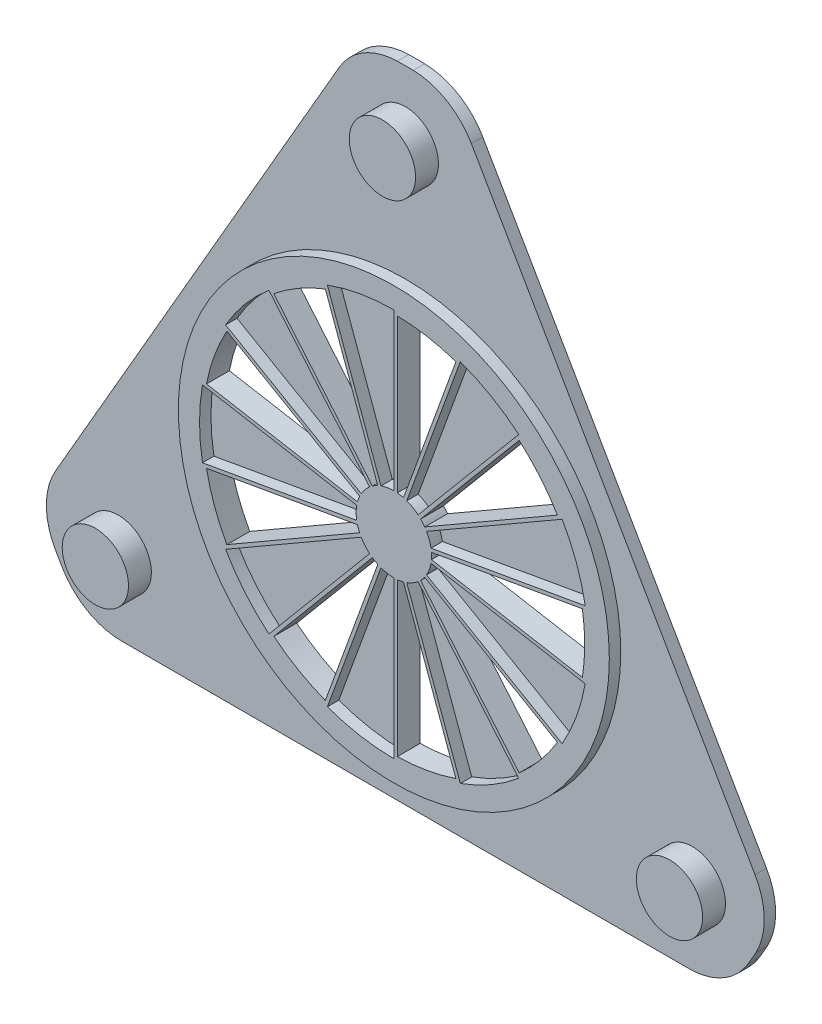
SolidWorks part; units mm, degrees
ref_plane "Спереди" through (0, 0, 0) normal (0, 0, 1) x (1, 0, 0)
ref_plane "Сверху" through (0, 0, 0) normal (0, 1, 0) x (1, 0, 0)
ref_plane "Справа" through (0, 0, 0) normal (1, 0, 0) x (0, 0, -1)
sketch "Sketch1" plane through (0, 0, 0) normal (0, 0, 1) x (1, 0, 0)
  line L0 (3.9, 6.755) -> (7.8, 0) construction
  line L2 (5.85, 10.1325) -> (11.7, 0) construction
  line L4 (7.8, 13.51) -> (15.6, 0) construction
  circle A61 centre (0, 0) radius 20
  circle A131 centre (0, 0) radius 1.25
  circle A484 centre (3.9, 0) radius 1.25
  circle A485 centre (7.8, 0) radius 1.25
  circle A486 centre (11.7, 0) radius 1.25
  circle A487 centre (15.6, 0) radius 1.25
  circle A488 centre (1.95, -3.3775) radius 1.25
  circle A489 centre (3.9, -6.755) radius 1.25
  circle A490 centre (5.85, -10.1325) radius 1.25
  circle A491 centre (7.8, -13.51) radius 1.25
  circle A492 centre (-1.95, -3.3775) radius 1.25
  circle A493 centre (-3.9, -6.755) radius 1.25
  circle A494 centre (-5.85, -10.1325) radius 1.25
  circle A495 centre (-7.8, -13.51) radius 1.25
  circle A496 centre (-3.9, 0) radius 1.25
  circle A497 centre (-7.8, 0) radius 1.25
  circle A498 centre (-11.7, 0) radius 1.25
  circle A499 centre (-15.6, 0) radius 1.25
  circle A500 centre (-1.95, 3.3775) radius 1.25
  circle A501 centre (-3.9, 6.755) radius 1.25
  circle A502 centre (-5.85, 10.1325) radius 1.25
  circle A503 centre (-7.8, 13.51) radius 1.25
  circle A504 centre (1.95, 3.3775) radius 1.25
  circle A505 centre (3.9, 6.755) radius 1.25
  circle A506 centre (5.85, 10.1325) radius 1.25
  circle A507 centre (7.8, 13.51) radius 1.25
  circle A508 centre (5.85, 3.3775) radius 1.25
  circle A509 centre (7.8, 6.755) radius 1.25
  circle A510 centre (9.75, 3.3775) radius 1.25
  circle A511 centre (11.7, 6.755) radius 1.25
  circle A512 centre (9.7491, 10.1341) radius 1.25
  circle A513 centre (13.6509, 3.3759) radius 1.25
  circle A514 centre (5.85, -3.3791) radius 1.25
  circle A515 centre (9.75, -3.3791) radius 1.25
  circle A516 centre (7.8, -6.7566) radius 1.25
  circle A517 centre (11.7, -6.7566) radius 1.25
  circle A518 centre (9.7491, -10.1356) radius 1.25
  circle A519 centre (13.6509, -3.3775) radius 1.25
  circle A520 centre (-0.0013, -6.7573) radius 1.25
  circle A521 centre (1.9487, -10.1348) radius 1.25
  circle A522 centre (-1.9513, -10.1348) radius 1.25
  circle A523 centre (-0.0013, -13.5123) radius 1.25
  circle A524 centre (-3.9032, -13.5123) radius 1.25
  circle A525 centre (3.9005, -13.5123) radius 1.25
  circle A526 centre (-5.8527, -3.3791) radius 1.25
  circle A527 centre (-7.8027, -6.7566) radius 1.25
  circle A528 centre (-9.7527, -3.3791) radius 1.25
  circle A529 centre (-11.7027, -6.7566) radius 1.25
  circle A530 centre (-13.6536, -3.3775) radius 1.25
  circle A531 centre (-9.7518, -10.1356) radius 1.25
  circle A532 centre (-5.8527, 3.3775) radius 1.25
  circle A533 centre (-9.7527, 3.3775) radius 1.25
  circle A534 centre (-7.8027, 6.755) radius 1.25
  circle A535 centre (-11.7027, 6.755) radius 1.25
  circle A536 centre (-9.7518, 10.1341) radius 1.25
  circle A537 centre (-13.6536, 3.3759) radius 1.25
  circle A538 centre (-0.0014, 6.7558) radius 1.25
  circle A539 centre (-1.9514, 10.1333) radius 1.25
  circle A540 centre (1.9486, 10.1333) radius 1.25
  circle A541 centre (-0.0014, 13.5108) radius 1.25
  circle A542 centre (3.9005, 13.5108) radius 1.25
  circle A543 centre (-3.9032, 13.5108) radius 1.25
  circle A544 centre (13.65, -1.1258) radius 2.2517 construction
  circle A545 centre (11.7009, -4.5044) radius 2.2522 construction
  circle A546 centre (9.75, -7.8834) radius 2.2522 construction
  circle A547 centre (7.7987, -11.2591) radius 2.2509 construction
  circle A548 centre (13.65, -1.1258) radius 0.65
  circle A549 centre (11.7009, -4.5044) radius 0.65
  circle A550 centre (9.75, -7.8834) radius 0.65
  circle A551 centre (7.7987, -11.2591) radius 0.65
  circle A552 centre (9.75, -1.1258) radius 0.65
  circle A553 centre (7.8009, -4.5044) radius 0.65
  circle A554 centre (5.85, -7.8834) radius 0.65
  circle A555 centre (3.8987, -11.2591) radius 0.65
  circle A556 centre (5.85, -1.1258) radius 0.65
  circle A557 centre (3.9009, -4.5044) radius 0.65
  circle A558 centre (1.95, -7.8834) radius 0.65
  circle A559 centre (-0.0013, -11.2591) radius 0.65
  circle A560 centre (1.95, -1.1258) radius 0.65
  circle A561 centre (0.0009, -4.5044) radius 0.65
  circle A562 centre (-1.95, -7.8834) radius 0.65
  circle A563 centre (-3.9013, -11.2591) radius 0.65
  circle A564 centre (-1.95, -1.1258) radius 0.65
  circle A565 centre (-3.8991, -4.5044) radius 0.65
  circle A566 centre (-5.85, -7.8834) radius 0.65
  circle A567 centre (-7.8013, -11.2591) radius 0.65
  circle A568 centre (-5.85, -1.1258) radius 0.65
  circle A569 centre (-7.7991, -4.5044) radius 0.65
  circle A570 centre (-9.75, -7.8834) radius 0.65
  circle A572 centre (-9.75, -1.1258) radius 0.65
  circle A573 centre (-11.6991, -4.5044) radius 0.65
  circle A576 centre (-13.65, -1.1258) radius 0.65
  circle A587 centre (0, 2.2517) radius 2.2517 construction
  circle A588 centre (0, 2.2517) radius 0.65
  circle A589 centre (3.9, 2.2517) radius 0.65
  circle A590 centre (7.8, 2.2517) radius 0.65
  circle A591 centre (11.7, 2.2517) radius 0.65
  circle A592 centre (15.6, 2.2517) radius 0.65
  circle A593 centre (1.9491, 5.6297) radius 2.2522 construction
  circle A594 centre (1.9491, 5.6297) radius 0.65
  circle A595 centre (5.8491, 5.6297) radius 0.65
  circle A596 centre (9.7491, 5.6297) radius 0.65
  circle A597 centre (13.6491, 5.6297) radius 0.65
  circle A598 centre (3.8991, 9.0072) radius 2.2522 construction
  circle A599 centre (3.8991, 9.0072) radius 0.65
  circle A600 centre (7.7991, 9.0072) radius 0.65
  circle A601 centre (11.6991, 9.0072) radius 0.65
  circle A602 centre (5.85, 12.3842) radius 2.2517 construction
  circle A603 centre (5.85, 12.3842) radius 0.65
  circle A604 centre (9.75, 12.3842) radius 0.65
  circle A605 centre (5.85, -14.6358) radius 0.65
  circle A606 centre (1.9509, -14.6353) radius 0.65
  circle A607 centre (-1.9491, -14.6353) radius 0.65
  circle A608 centre (-5.85, -14.6358) radius 0.65
  circle A609 centre (-15.6, 2.2517) radius 0.65
  circle A610 centre (-13.65, 5.6281) radius 0.65
  circle A611 centre (-11.7, 9.0056) radius 0.65
  circle A612 centre (-9.75, 12.3842) radius 0.65
  circle A613 centre (-5.85, 12.3842) radius 0.65
  circle A614 centre (-1.95, 12.3842) radius 0.65
  circle A615 centre (1.95, 12.3842) radius 0.65
  circle A616 centre (-7.8, 9.0056) radius 0.65
  circle A617 centre (-9.75, 5.6281) radius 0.65
  circle A618 centre (-11.7, 2.2517) radius 0.65
  circle A619 centre (-3.9, 9.0056) radius 0.65
  circle A620 centre (-5.85, 5.6281) radius 0.65
  circle A621 centre (-7.8, 2.2517) radius 0.65
  circle A622 centre (0, 9.0056) radius 0.65
  circle A623 centre (-1.95, 5.6281) radius 0.65
  circle A624 centre (-3.9, 2.2517) radius 0.65
  circle A625 centre (-15.5991, -4.5044) radius 0.65
  circle A626 centre (-13.65, -7.8834) radius 0.65
  circle A627 centre (-17.55, -7.8834) radius 0.65
  circle A628 centre (-19.5013, -11.2591) radius 0.65
  circle A629 centre (-15.6013, -11.2591) radius 0.65
  circle A630 centre (-11.7013, -11.2591) radius 0.65
  point P51 (0, 0)
  point P125 (-0.0013, -0.0008)
  point P231 (0, 0)
  dimension "D1" = 5
  dimension "D3" = 6
  dimension "D5" = 8
  dimension "D7" = 4
  dimension "D11" = 4
  dimension "D2" = 6
  dimension "D6" = 5
  dimension "D8" = 3
  dimension "D9" = 2
  dimension "D4" = 1.3
  dimension "D10" = 3
ref_plane "Plane1" through (0, 0, 10) normal (0, 0, 1) x (1, 0, 0)
sketch "Sketch2" plane through (0, 0, 10) normal (0, 0, 1) x (1, 0, 0)
  line L0 (0, 2.9883) -> (0, 17)
  line L62 (1.0221, 2.8081) -> (5.8143, 15.9748)
  line L71 (1.9208, 2.2892) -> (10.9274, 13.0228)
  line L92 (2.588, 1.4942) -> (14.7224, 8.5)
  line L101 (2.9429, 0.5189) -> (16.7417, 2.952)
  line L110 (2.9429, -0.5189) -> (16.7417, -2.952)
  line L119 (2.588, -1.4942) -> (14.7224, -8.5)
  line L124 (1.9208, -2.2892) -> (10.9274, -13.0228)
  line L133 (1.0221, -2.8081) -> (5.8143, -15.9748)
  line L142 (0, -2.9883) -> (0, -17)
  line L151 (-1.0221, -2.8081) -> (-5.8143, -15.9748)
  line L160 (-1.9208, -2.2892) -> (-10.9274, -13.0228)
  line L165 (-2.588, -1.4942) -> (-14.7224, -8.5)
  line L168 (-2.9429, -0.5189) -> (-16.7417, -2.952)
  line L171 (-2.9429, 0.5189) -> (-16.7417, 2.952)
  line L174 (-2.588, 1.4942) -> (-14.7224, 8.5)
  line L177 (-1.9208, 2.2892) -> (-10.9274, 13.0228)
  line L180 (-1.0221, 2.8081) -> (-5.8143, 15.9748)
  line L183 (0.3, 3.2863) -> (0.3, 16.6948)
  line L185 (5.4281, 15.7906) -> (0.8421, 3.1908)
  line L186 (14.3082, 8.6072) -> (2.696, 1.903)
  line L187 (2.3422, 2.3246) -> (10.9611, 12.5962)
  line L188 (16.4933, -2.6036) -> (3.2885, -0.2752)
  line L189 (3.2885, 0.2752) -> (16.4933, 2.6036)
  line L190 (10.9611, -12.5962) -> (2.3422, -2.3246)
  line L191 (2.696, -1.903) -> (14.3082, -8.6072)
  line L192 (0.3, -16.6948) -> (0.3, -3.2863)
  line L193 (0.8421, -3.1908) -> (5.4281, -15.7906)
  line L194 (-10.5014, -12.9818) -> (-1.8826, -2.7103)
  line L195 (-1.4059, -2.9855) -> (-5.9919, -15.5854)
  line L196 (-16.3891, -3.1945) -> (-3.1843, -0.8661)
  line L197 (-2.996, -1.3834) -> (-14.6082, -8.0876)
  line L198 (-14.6082, 8.0876) -> (-2.996, 1.3834)
  line L199 (-3.1843, 0.8661) -> (-16.3891, 3.1945)
  line L200 (-5.9919, 15.5854) -> (-1.4059, 2.9855)
  line L201 (-1.8826, 2.7103) -> (-10.5014, 12.9818)
  circle A52 centre (0, 0) radius 17
  circle A53 centre (0, 0) radius 18.85
  circle A199 centre (0, 0) radius 2.9883
  circle A245 centre (0, 0) radius 18.85
  circle A246 centre (0, 0) radius 3.3
  circle A247 centre (0, 0) radius 16.6975
  point P39 (0, 0)
  point P80 (0, 0)
  point P108 (0, 0)
  dimension "D1" = 18
  dimension "D4" = 9
  dimension "D2" = 0.3
  dimension "D3" = 0.3
extrude "Boss-Extrude1" add sketch "Sketch2" against normal blind 2
sketch "Sketch11" plane through (0, 0, 8) normal (0, 0, -1) x (-1, 0, 0)
  line L0 (0, 2.9883) -> (0, 18.85)
  line L1 (1.0221, 2.8081) -> (6.4471, 17.7132)
  line L2 (2.588, 1.4942) -> (16.3246, 9.425)
  line L3 (1.9208, 2.2892) -> (12.1165, 14.4399)
  line L4 (2.9429, -0.5189) -> (18.5636, -3.2733)
  line L5 (2.9429, 0.5189) -> (18.5636, 3.2733)
  line L6 (1.9208, -2.2892) -> (12.1165, -14.4399)
  line L7 (2.588, -1.4942) -> (16.3246, -9.425)
  line L8 (0, -2.9883) -> (0, -18.85)
  line L9 (1.0221, -2.8081) -> (6.4471, -17.7132)
  line L10 (-1.9208, -2.2892) -> (-12.1165, -14.4399)
  line L11 (-1.0221, -2.8081) -> (-6.4471, -17.7132)
  line L12 (-2.9429, -0.5189) -> (-18.5636, -3.2733)
  line L13 (-2.588, -1.4942) -> (-16.3246, -9.425)
  line L14 (-2.588, 1.4942) -> (-16.3246, 9.425)
  line L15 (-2.9429, 0.5189) -> (-18.5636, 3.2733)
  line L16 (-1.0221, 2.8081) -> (-6.4471, 17.7132)
  line L17 (-1.9208, 2.2892) -> (-12.1165, 14.4399)
  circle A0 centre (0, 0) radius 2.9883
  circle A5 centre (0, 0) radius 18.85 construction
  arc A6 (0, 18.85) -> (6.4471, 17.7132) centre (0, 0) cw
  arc A8 (12.1165, 14.4399) -> (16.3246, 9.425) centre (0, 0) cw
  arc A10 (18.5636, 3.2733) -> (18.5636, -3.2733) centre (0, 0) cw
  arc A12 (16.3246, -9.425) -> (12.1165, -14.4399) centre (0, 0) cw
  arc A14 (6.4471, -17.7132) -> (0, -18.85) centre (0, 0) cw
  arc A16 (-6.4471, -17.7132) -> (-12.1165, -14.4399) centre (0, 0) cw
  arc A18 (-16.3246, -9.425) -> (-18.5636, -3.2733) centre (0, 0) cw
  arc A20 (-18.5636, 3.2733) -> (-16.3246, 9.425) centre (0, 0) cw
  arc A22 (-12.1165, 14.4399) -> (-6.4471, 17.7132) centre (0, 0) cw
  point P63 (0, 0)
  dimension "D1" = 9
extrude "Boss-Extrude7" add sketch "Sketch11" against normal blind 1 contours A8 L3 A0 L2 | A10 L5 A0 L4 | A12 L7 A0 L6 | A14 L9 A0 L8 | A16 L11 A0 L10 | A18 L13 A0 L12 | A20 L15 A0 L14 | A22 L17 A0 L16 | A6 L0 A0 L1
sketch "Sketch13" plane through (0, 0, 8) normal (0, 0, -1) x (-1, 0, 0)
  circle A0 centre (0, 0) radius 3.3
extrude "Boss-Extrude8" [suppressed] add sketch "Sketch13" against normal blind 3
sketch "Sketch14" plane through (0, 0, 10) normal (0, 0, 1) x (1, 0, 0)
  circle A0 centre (0, 0) radius 17
  arc A1 (0, 17) -> (-5.8143, 15.9748) centre (0, 0) ccw construction
sketch "Sketch9" plane through (0, 0, 10) normal (0, 0, 1) x (1, 0, 0)
  circle A0 centre (0, 0) radius 3.0981
sketch "Sketch16" plane through (0, 0, 9) normal (0, 0, 1) x (1, 0, 0)
  circle A0 centre (0, 0) radius 3.3
sketch "Sketch17" plane through (0, 0, 8) normal (0, 0, -1) x (-1, 0, 0)
  circle A0 centre (0, 0) radius 3.3
extrude "Boss-Extrude9" add sketch "Sketch17" against normal blind 2
extrude "Boss-Extrude5" add sketch "Sketch9" against normal up to surface (2 mm away)
sketch "Sketch3" plane through (0, 0, 8) normal (0, 0, -1) x (-1, 0, 0)
  circle A0 centre (0, 0) radius 17.6
  circle A1 centre (0, 0) radius 35
  circle M33 centre (0, 0) radius 18.85
extrude "Boss-Extrude2" add sketch "Sketch3" against normal blind 1 contours A1 M33
sketch "Sketch4" plane through (0, 0, 8) normal (0, 0, -1) x (-1, 0, 0)
  circle A0 centre (0, 0) radius 29 construction
  circle A1 centre (0, 29) radius 2.9
  circle A2 centre (25.1147, -14.5) radius 2.9
  circle A3 centre (-25.1147, -14.5) radius 2.9
  point P11 (0, 0)
  dimension "D1" = 3
extrude "Boss-Extrude3" add sketch "Sketch4" against normal blind 3
sketch "Sketch6" plane through (0, 0, 9) normal (0, 0, -1) x (-1, 0, 0)
  circle A0 centre (0, 30) radius 5
  circle A2 centre (25.9808, -15) radius 5
  circle A3 centre (-25.9808, -15) radius 5
  point P10 (0, 0)
  dimension "D1" = 3
extrude "Boss-Extrude4" add sketch "Sketch6" along normal blind 1
sketch "Sketch7" plane through (0, 0, 8) normal (0, 0, -1) x (-1, 0, 0)
  line L1 (0, 42) -> (-36.3731, -21)
  line L2 (-36.3731, -21) -> (36.3731, -21)
  line L3 (36.3731, -21) -> (0, 42)
  circle A2 centre (0, 0) radius 21 construction
  circle A3 centre (0, 0) radius 59.1314
extrude "Cut-Extrude1" cut sketch "Sketch7" against normal blind 10
fillet "Fillet1" radius 6 6 edges at (-32.1865, -13.7487, 8.5) (-4.1865, 34.7487, 8.5) (28, -21, 8.5) (-28, -21, 8.5) (4.1865, 34.7487, 8.5) (32.1865, -13.7487, 8.5)
